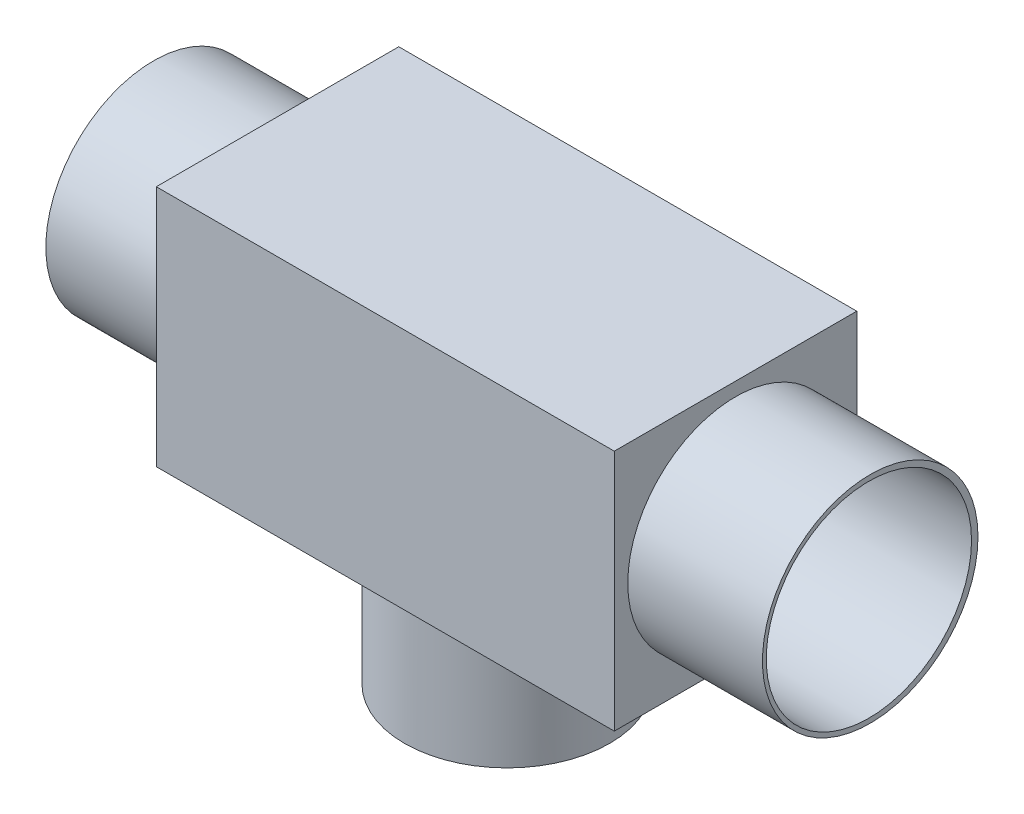
SolidWorks part; units mm, degrees
ref_plane "Alzado" through (0, 0, 0) normal (0, 0, 1) x (1, 0, 0)
ref_plane "Planta" through (0, 0, 0) normal (0, 1, 0) x (1, 0, 0)
ref_plane "Vista lateral" through (0, 0, 0) normal (1, 0, 0) x (0, 0, -1)
sketch "Croquis1" plane through (0, 0, 0) normal (0, 0, 1) x (1, 0, 0)
  line L1 (42.5, -22.5) -> (-42.5, -22.5)
  line L2 (42.5, -22.5) -> (42.5, 22.5)
  line L3 (42.5, 22.5) -> (-42.5, 22.5)
  line L4 (-42.5, -22.5) -> (-42.5, 22.5)
  line L5 (42.5, -22.5) -> (-42.5, 22.5) construction
  line L6 (42.5, 22.5) -> (-42.5, -22.5) construction
  point P0 (0, 0)
  dimension "D1" = 85
  dimension "D2" = 45
extrude "Saliente-Extruir1" add sketch "Croquis1" along normal blind 45
sketch "Croquis2" plane through (42.5, 0, 0) normal (1, 0, 0) x (0, 0, -1)
  circle A0 centre (-22.5, 0) radius 20
  dimension "D2" = 40
  dimension "D1" = 22.5
extrude "Saliente-Extruir2" add sketch "Croquis2" along normal blind 25 and the other way blind 108
sketch "Croquis5" plane through (67.5, 0, 0) normal (1, 0, 0) x (0, 0, -1)
  circle A0 centre (-22.75, 0) radius 19.05
  dimension "D1" = 38.1
sketch "Croquis7" plane through (0, -22.5, 0) normal (0, -1, 0) x (1, 0, 0)
  line L1 (-42.5, 45) -> (-42.5, 0) construction
  circle A0 centre (0, 22.3958) radius 19.05
  dimension "D1" = 38.1
  dimension "D2" = 42.5
extrude "Saliente-Extruir3" add sketch "Croquis7" along normal blind 25
sketch "Croquis10" plane through (0, -47.5, 0) normal (0, -1, 0) x (-1, 0, 0)
  circle A0 centre (0, -22.6458) radius 16.9619
  circle A1 centre (0, -22.3958) radius 19.05 construction
  dimension "D1" = 0.25
extrude "Cortar-Extruir2" cut sketch "Croquis10" against normal blind 45
sketch "Croquis12" plane through (67.5, 0, 0) normal (1, 0, 0) x (0, 0, -1)
  circle A0 centre (-22.75, 0) radius 19.05
  dimension "D1" = 38.1
extrude "Cortar-Extruir3" cut sketch "Croquis12" against normal blind 159
